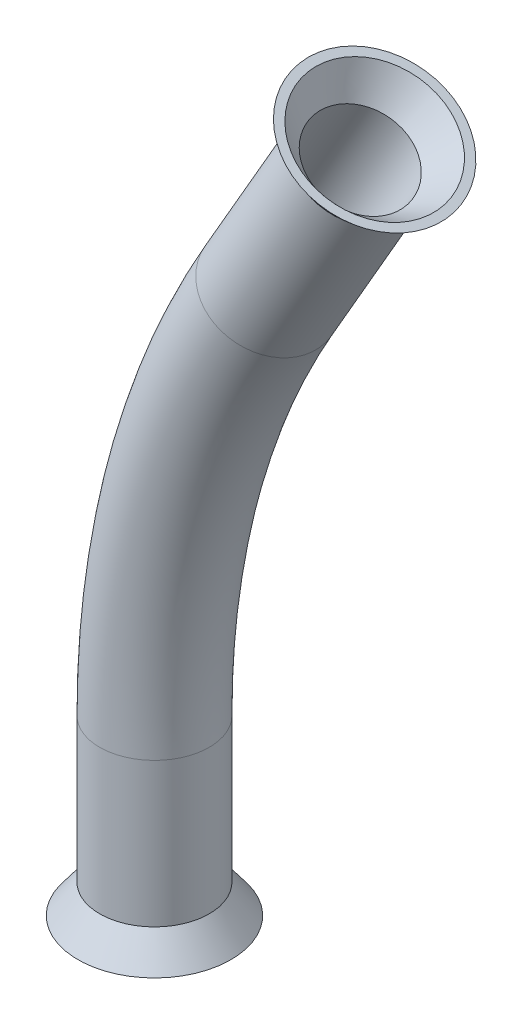
SolidWorks part; units mm, degrees
material "6061-T6 (SS)"
ref_plane "Front Plane" through (0, 0, 0) normal (0, 0, 1) x (1, 0, 0)
ref_plane "Top Plane" through (0, 0, 0) normal (0, 1, 0) x (1, 0, 0)
ref_plane "Right Plane" through (0, 0, 0) normal (1, 0, 0) x (0, 0, -1)
sketch "Sketch1" plane through (0, 0, 0) normal (0, 1, 0) x (1, 0, 0)
  circle A0 centre (0, 0) radius 4.826
  circle A1 centre (0, 0) radius 4.064
  dimension "D1" = 9.652
  dimension "D2" = 8.128
sketch "Sketch2" plane through (0, 0, 0) normal (0, 0, 1) x (1, 0, 0)
  line L0 (0, 0) -> (0, 12.7)
  line L1 (10.023, 50.1064) -> (18.1224, 64.135)
  arc A0 (0, 12.7) -> (10.023, 50.1064) centre (74.8129, 12.7) cw
  point P5 (5.9327, 43.0218)
  dimension "D1" = 18.1224
  dimension "D2" = 150
  dimension "D4" = 64.135
  dimension "D3" = 12.7
sweep "Sweep1" add profiles "Sketch1" path "Sketch2"
sketch "Sketch3" plane through (0, 0, 0) normal (0, -1, 0) x (1, 0, 0)
  circle A0 centre (0, 0) radius 4.826
  circle A1 centre (0, 0) radius 4.826 construction
extrude "Boss-Extrude1" add sketch "Sketch3" along normal blind 2.54 draft 37 draft outward yes
sketch "Sketch4" plane through (0, -2.54, 0) normal (0, -1, 0) x (1, 0, 0)
  line L0 (-4.826, 0) -> (-4.064, 0) construction
  line L1 (-5.978, 0) -> (-6.74, 0) construction
  circle A0 centre (0, 0) radius 5.978
  circle A1 centre (0, 0) radius 4.826 construction
  circle A2 centre (0, 0) radius 4.064 construction
  circle A3 centre (0, 0) radius 6.74 construction
extrude "Cut-Extrude1" cut sketch "Sketch4" against normal through all draft 37
sketch "Sketch5" plane through (32.3019, 55.9485, 0) normal (0.5, 0.866, 0) x (0, 0, -1)
  circle A1 centre (0, 16.373) radius 4.826
  circle A2 centre (0, 16.373) radius 4.826 construction
  circle A3 centre (0, 16.373) radius 4.826 construction
extrude "Boss-Extrude2" add sketch "Sketch5" along normal blind 2.54 draft 37 draft outward yes
sketch "Sketch6" plane through (33.5719, 58.1482, 0) normal (0.5, 0.866, 0) x (0, 0, -1)
  line L0 (-5.978, 16.373) -> (-6.74, 16.373) construction
  circle A0 centre (0, 16.373) radius 5.978
  circle A1 centre (0, 16.373) radius 6.74 construction
  dimension "D1" = 0.762
extrude "Cut-Extrude2" cut sketch "Sketch6" against normal through all draft 37
